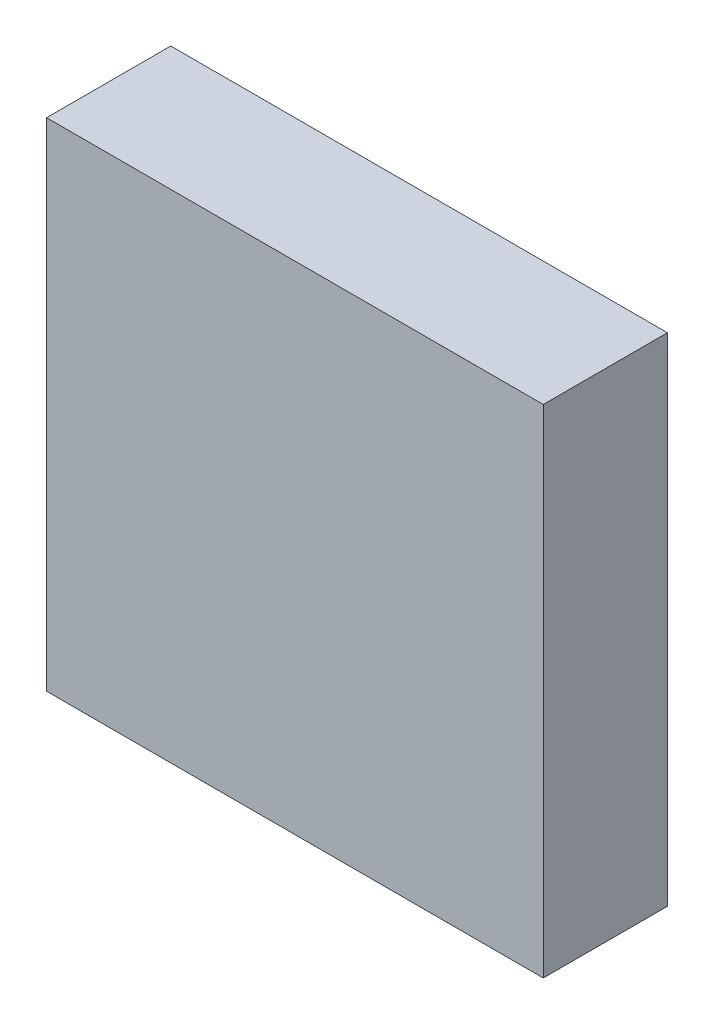
SolidWorks part; units mm, degrees
ref_plane "Face" through (0, 0, 0) normal (0, 0, 1) x (1, 0, 0)
ref_plane "Dessus" through (0, 0, 0) normal (0, 1, 0) x (1, 0, 0)
ref_plane "Droite" through (0, 0, 0) normal (1, 0, 0) x (0, 0, -1)
sketch "Esquisse1" plane through (0, 0, 0) normal (0, 0, 1) x (1, 0, 0)
  line L1 (-100, 100) -> (100, 100)
  line L2 (-100, 100) -> (-100, -100)
  line L3 (-100, -100) -> (100, -100)
  line L4 (100, 100) -> (100, -100)
extrude "Extrusion1" add sketch "Esquisse1" along normal blind 50
sketch "Esquisse2" plane through (0, 0, 0) normal (1, 0, 0) x (0, 0, -1)
  line L0 (0, 0) -> (729.8348, 0) construction
  point P0 (685.588, 0)
